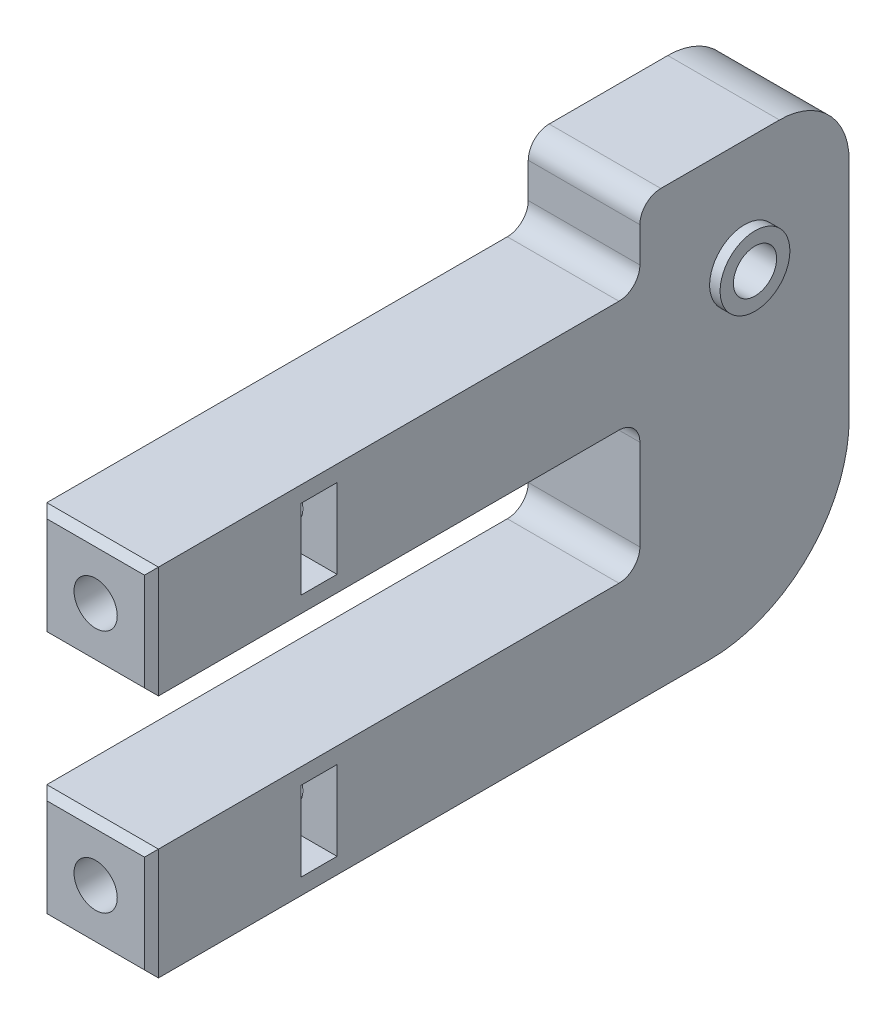
SolidWorks part; units mm, degrees
ref_plane "Front Plane" through (0, 0, 0) normal (0, 0, 1) x (1, 0, 0)
ref_plane "Top Plane" through (0, 0, 0) normal (0, 1, 0) x (1, 0, 0)
ref_plane "Right Plane" through (0, 0, 0) normal (1, 0, 0) x (0, 0, -1)
sketch "Sketch1" plane through (0, 0, 0) normal (1, 0, 0) x (0, 0, -1)
  line L0 (0, 0) -> (50, 0)
  line L1 (50, 0) -> (50, 31)
  line L2 (50, 31) -> (35, 31)
  line L3 (35, 31) -> (35, 25.5)
  line L4 (35, 25.5) -> (0, 25.5)
  line L5 (0, 25.5) -> (0, 17.5)
  line L6 (0, 17.5) -> (35, 17.5)
  line L7 (35, 17.5) -> (35, 8)
  line L8 (35, 8) -> (0, 8)
  line L9 (0, 8) -> (0, 0)
  line L10 (0, 21.5) -> (10, 21.5) construction
  line L11 (0, 4) -> (10, 4) construction
  line L12 (10, 21.5) -> (10, 4) construction
  line L13 (10, 12.75) -> (42.5, 12.75) construction
  line L14 (42.5, 12.75) -> (42.5, 23.25) construction
  circle A0 centre (42.5, 23.25) radius 1.55
  dimension "D12" = 3.1
  dimension "D1" = 15
  dimension "D2" = 8
  dimension "D3" = 8
  dimension "D4" = 10
  dimension "D5" = 10
  dimension "D6" = 17.5
  dimension "D7" = 35
  dimension "D8" = 50
  dimension "D9" = 32.5
  dimension "D10" = 10.5
  dimension "D11" = 31
extrude "Boss-Extrude1" add sketch "Sketch1" along normal blind 8
sketch "Sketch4" plane through (0, 0, 0) normal (0, 0, 1) x (1, 0, 0)
  line L0 (0, 25.5) -> (8, 17.5) construction
  line L1 (8, 8) -> (0, 0) construction
  circle A0 centre (4, 21.5) radius 1.55
  circle A1 centre (4, 4) radius 1.55
  dimension "D1" = 3.1
  dimension "D2" = 3.1
extrude "Cut-Extrude2" cut sketch "Sketch4" against normal blind 20
sketch "Sketch5" plane through (0, 0, 0) normal (-1, 0, 0) x (0, 0, 1)
  line L0 (0, 21.5) -> (-12, 21.5) construction
  line L1 (0, 25.5) -> (0, 17.5) construction
  line L2 (0, 4) -> (-12, 4) construction
  line L3 (0, 8) -> (0, 0) construction
  line L5 (-13.3, 18.65) -> (-10.7, 18.65)
  line L6 (-13.3, 18.65) -> (-13.3, 24.35)
  line L7 (-13.3, 24.35) -> (-10.7, 24.35)
  line L8 (-10.7, 18.65) -> (-10.7, 24.35)
  line L9 (-13.3, 18.65) -> (-10.7, 24.35) construction
  line L10 (-13.3, 24.35) -> (-10.7, 18.65) construction
  line L11 (-13.3, 1.15) -> (-10.7, 1.15)
  line L12 (-13.3, 1.15) -> (-13.3, 6.85)
  line L13 (-13.3, 6.85) -> (-10.7, 6.85)
  line L14 (-10.7, 1.15) -> (-10.7, 6.85)
  line L15 (-13.3, 1.15) -> (-10.7, 6.85) construction
  line L16 (-13.3, 6.85) -> (-10.7, 1.15) construction
  dimension "D1" = 12
  dimension "D2" = 12
  dimension "D3" = 2.6
  dimension "D4" = 5.7
  dimension "D5" = 2.6
  dimension "D6" = 5.7
extrude "Cut-Extrude3" cut sketch "Sketch5" against normal through all
fillet "Fillet2" radius 1.5 4 edges at (4, 31, -35) (4, 25.5, -35) (4, 8, -35) (4, 17.5, -35)
fillet "Fillet3" radius 5 1 edges at (4, 31, -50)
fillet "Fillet4" radius 10 1 edges at (4, 0, -50)
chamfer "Chamfer1" distance 0.5 angle 45 8 edges at (0, 4, 0) (4, 0, 0) (8, 4, 0) (4, 8, 0) (4, 17.5, 0) (0, 21.5, 0) (8, 21.5, 0) (4, 25.5, 0)
sketch "Sketch6" plane through (8, 0, 0) normal (1, 0, 0) x (0, 0, -1)
  circle A0 centre (42.5, 23.25) radius 1.55
  circle A1 centre (42.5, 23.25) radius 2.5
  dimension "D1" = 3.1
  dimension "D2" = 5
extrude "Boss-Extrude3" add sketch "Sketch6" along normal blind 0.75
sketch "Sketch7" plane through (0, 0, 0) normal (-1, 0, 0) x (0, 0, 1)
  line L0 (-42.5, 23.25) -> (-36.5, 23.25) construction
  line L1 (-42.5, 23.25) -> (-39.7504, 24.8375) construction
  line L2 (-39.7504, 24.8375) -> (-42.5, 26.425)
  line L3 (-42.5, 26.425) -> (-45.2496, 24.8375)
  line L4 (-45.2496, 24.8375) -> (-45.2496, 21.6625)
  line L5 (-45.2496, 21.6625) -> (-42.5, 20.075)
  line L6 (-42.5, 20.075) -> (-39.7504, 21.6625)
  line L7 (-39.7504, 21.6625) -> (-39.7504, 24.8375)
  circle A0 centre (-42.5, 23.25) radius 3.175 construction
  dimension "D2" = 6.35
  dimension "D1" = 6
  dimension "D3" = 30
extrude "Cut-Extrude4" cut sketch "Sketch7" against normal blind 4
